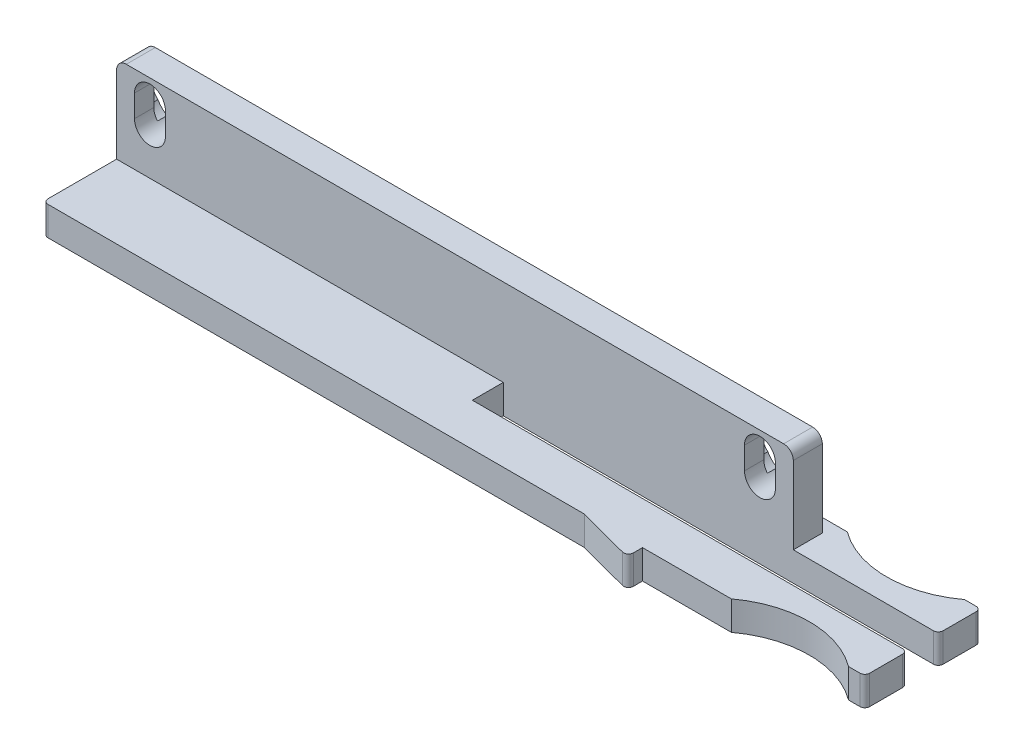
SolidWorks part; units mm, degrees
ref_plane "正面" through (0, 0, 0) normal (0, 0, 1) x (1, 0, 0)
ref_plane "平面" through (0, 0, 0) normal (0, 1, 0) x (1, 0, 0)
ref_plane "右側面" through (0, 0, 0) normal (1, 0, 0) x (0, 0, -1)
sketch "ｽｹｯﾁ2" plane through (0, 0, 0) normal (0, 1, 0) x (1, 0, 0)
  line L0 (70, 7.6) -> (40, 7.6)
  line L1 (0.5, 0) -> (56, 0)
  line L2 (0, 0.5) -> (0, 11.5)
  line L3 (0.5, 12) -> (70, 12)
  line L5 (40, 7.6) -> (40, 4.4)
  line L6 (40, 4.4) -> (70, 4.4)
  line L8 (56, 0) -> (61.3712, -1.4323)
  line L9 (62, -0.9492) -> (62, 0)
  line L10 (62, 0) -> (70, 0)
  line L11 (70, 12) -> (71.1837, 12)
  line L12 (85, 11.5) -> (85, 8.1)
  line L13 (84.5, 7.6) -> (70, 7.6)
  line L14 (70, 4.4) -> (84.5, 4.4)
  line L15 (85, 3.9) -> (85, 0.5)
  line L16 (84.5, 0) -> (83.3163, 0)
  line L17 (77.25, 12) -> (77.25, 20.2) construction
  line L18 (77.25, 12) -> (77.25, 10) construction
  line L19 (0, 6) -> (85, 6) construction
  line L20 (77.25, 0) -> (77.25, 2) construction
  line L21 (77.25, 0) -> (77.25, -8.2) construction
  line L22 (71.1837, 0) -> (70, 0)
  line L23 (83.3163, 12) -> (84.5, 12)
  arc A0 (61.3712, -1.4323) -> (62, -0.9492) centre (61.5, -0.9492) ccw
  arc A1 (71.1837, 12) -> (83.3163, 12) centre (77.25, 20.2) ccw
  arc A2 (71.1837, 0) -> (83.3163, 0) centre (77.25, -8.2) cw
  arc A3 (84.5, 12) -> (85, 11.5) centre (84.5, 11.5) cw
  arc A4 (85, 0.5) -> (84.5, 0) centre (84.5, 0.5) cw
  arc A5 (84.5, 4.4) -> (85, 3.9) centre (84.5, 3.9) cw
  arc A6 (85, 8.1) -> (84.5, 7.6) centre (84.5, 8.1) cw
  arc A7 (0.5, 0) -> (0, 0.5) centre (0.5, 0.5) cw
  arc A8 (0, 11.5) -> (0.5, 12) centre (0.5, 11.5) cw
  point P14 (62, -1.6)
  point P33 (77.25, 4.4)
  point P35 (77.25, 7.6)
  point P39 (85, 12)
  point P46 (85, 7.6)
  point P49 (0, 0)
  point P52 (0, 12)
  dimension "D8" = 0.5
  dimension "D12" = 0.5
  dimension "D13" = 0.5
  dimension "D14" = 0.5
  dimension "D1" = 70
  dimension "D2" = 15
  dimension "D3" = 3.2
  dimension "D4" = 30
  dimension "D5" = 8
  dimension "D6" = 6
  dimension "6" = 1.6
  dimension "D9" = 12
  dimension "D10" = 2
  dimension "D11" = 8.2
extrude "ﾎﾞｽ - 押し出し1" add sketch "ｽｹｯﾁ2" along normal blind 3
sketch "ｽｹｯﾁ4" plane through (0, 3, 0) normal (0, 1, 0) x (1, 0, 0)
  line L0 (0, 11.5) -> (0, 0.5) construction
  line L1 (70, 7.6) -> (0, 7.6)
  line L2 (70, 7.6) -> (70, 10.6)
  line L3 (70, 10.6) -> (0, 10.6)
  line L4 (0, 7.6) -> (0, 10.6)
  line L5 (40, 7.6) -> (84.5, 7.6) construction
  dimension "D1" = 3
  dimension "D2" = 70
extrude "ﾎﾞｽ - 押し出し2" add sketch "ｽｹｯﾁ4" along normal blind 9
sketch "ｽｹｯﾁ5" plane through (0, 0, -7.6) normal (0, 0, 1) x (1, 0, 0)
  line L0 (35, 12) -> (35, 8.7) construction
  line L1 (0, 12) -> (70, 12) construction
  line L2 (35, 8.7) -> (35, 3) construction
  line L4 (0.5, 3) -> (56, 3) construction
  line L7 (4.6, 8.7) -> (65.4, 8.7) construction
  line L10 (65.4, 8.7) -> (67.7, 8.7) construction
  line L14 (4.6, 8.7) -> (2.3, 8.7) construction
  line L15 (66.55, 7.55) -> (66.55, 9.85) construction
  line L16 (3.45, 7.55) -> (3.45, 9.85) construction
  arc A8 (64.3707, 9.9249) -> (64.3707, 7.4751) centre (65.4, 8.7) ccw
  arc A9 (65.3251, 6.5207) -> (67.7749, 6.5207) centre (66.55, 7.55) ccw
  arc A11 (5.6293, 7.4751) -> (5.6293, 9.9249) centre (4.6, 8.7) ccw
  arc A12 (1.2707, 9.9249) -> (1.2707, 7.4751) centre (2.3, 8.7) ccw
  arc A13 (2.2251, 6.5207) -> (4.6749, 6.5207) centre (3.45, 7.55) ccw
  arc A14 (67.7749, 10.8793) -> (65.3251, 10.8793) centre (66.55, 9.85) ccw
  arc A16 (68.7293, 7.4751) -> (68.7293, 9.9249) centre (67.7, 8.7) ccw
  arc A18 (64.3707, 7.4751) -> (65.3251, 6.5207) centre (66.55, 8.7) ccw
  arc A19 (67.7749, 6.5207) -> (68.7293, 7.4751) centre (66.55, 8.7) ccw
  arc A20 (68.7293, 9.9249) -> (67.7749, 10.8793) centre (66.55, 8.7) ccw
  arc A21 (65.3251, 10.8793) -> (64.3707, 9.9249) centre (66.55, 8.7) ccw
  arc A22 (1.2707, 7.4751) -> (2.2251, 6.5207) centre (3.45, 8.7) ccw
  arc A26 (4.6749, 10.8793) -> (2.2251, 10.8793) centre (3.45, 9.85) ccw
  arc A27 (2.2251, 10.8793) -> (1.2707, 9.9249) centre (3.45, 8.7) ccw
  arc A28 (5.6293, 9.9249) -> (4.6749, 10.8793) centre (3.45, 8.7) ccw
  arc A29 (4.6749, 6.5207) -> (5.6293, 7.4751) centre (3.45, 8.7) ccw
  point P9 (35, 8.7)
  point P10 (3.45, 8.7)
  point P13 (66.55, 8.7)
  point P17 (66.55, 8.7)
  point P20 (3.45, 8.7)
  dimension "D3" = 2.3
  dimension "D5" = 1.6
  dimension "5" = 5
  dimension "D1" = 5.7
  dimension "D2" = 63.1
extrude "ｶｯﾄ - 押し出し1" cut sketch "ｽｹｯﾁ5" against normal up to next
fillet "ﾌｨﾚｯﾄ1" radius 1 2 edges at (70, 12, -9.1) (0, 12, -9.1)
sketch "ｽｹｯﾁ6" plane through (0, 0, -7.6) normal (0, 0, 1) x (1, 0, 0)
  line L0 (1.85, 9.85) -> (1.85, 7.55)
  line L1 (5.05, 9.85) -> (5.05, 7.55)
  line L2 (64.95, 9.85) -> (64.95, 7.55)
  line L3 (68.15, 9.85) -> (68.15, 7.55)
  arc A42 (5.05, 9.85) -> (4.6749, 10.8793) centre (3.45, 9.85) ccw
  arc A43 (1.85, 7.55) -> (2.2251, 6.5207) centre (3.45, 7.55) ccw
  arc A53 (4.6749, 6.5207) -> (5.6293, 7.4751) centre (3.45, 8.7) ccw
  arc A54 (5.6293, 7.4751) -> (5.6293, 9.9249) centre (4.6, 8.7) ccw
  arc A55 (5.6293, 9.9249) -> (4.6749, 10.8793) centre (3.45, 8.7) ccw
  arc A56 (4.6749, 6.5207) -> (5.6293, 7.4751) centre (3.45, 8.7) ccw
  arc A57 (5.6293, 7.4751) -> (5.6293, 9.9249) centre (4.6, 8.7) ccw
  arc A58 (5.6293, 9.9249) -> (4.6749, 10.8793) centre (3.45, 8.7) ccw
  arc A62 (2.2251, 10.8793) -> (1.85, 9.85) centre (3.45, 9.85) ccw
  arc A63 (4.6749, 6.5207) -> (5.05, 7.55) centre (3.45, 7.55) ccw
  arc A64 (68.15, 9.85) -> (67.7749, 10.8793) centre (66.55, 9.85) ccw
  arc A65 (1.2707, 7.4751) -> (2.2251, 6.5207) centre (3.45, 8.7) ccw
  arc A66 (1.2707, 9.9249) -> (1.2707, 7.4751) centre (2.3, 8.7) ccw
  arc A67 (2.2251, 10.8793) -> (1.2707, 9.9249) centre (3.45, 8.7) ccw
  arc A68 (1.2707, 7.4751) -> (2.2251, 6.5207) centre (3.45, 8.7) ccw
  arc A69 (1.2707, 9.9249) -> (1.2707, 7.4751) centre (2.3, 8.7) ccw
  arc A70 (2.2251, 10.8793) -> (1.2707, 9.9249) centre (3.45, 8.7) ccw
  arc A71 (64.95, 7.55) -> (65.3251, 6.5207) centre (66.55, 7.55) ccw
  arc A81 (64.3707, 7.4751) -> (65.3251, 6.5207) centre (66.55, 8.7) ccw
  arc A82 (64.3707, 9.9249) -> (64.3707, 7.4751) centre (65.4, 8.7) ccw
  arc A83 (65.3251, 10.8793) -> (64.3707, 9.9249) centre (66.55, 8.7) ccw
  arc A84 (64.3707, 7.4751) -> (65.3251, 6.5207) centre (66.55, 8.7) ccw
  arc A85 (64.3707, 9.9249) -> (64.3707, 7.4751) centre (65.4, 8.7) ccw
  arc A86 (65.3251, 10.8793) -> (64.3707, 9.9249) centre (66.55, 8.7) ccw
  arc A90 (65.3251, 10.8793) -> (64.95, 9.85) centre (66.55, 9.85) ccw
  arc A91 (67.7749, 6.5207) -> (68.15, 7.55) centre (66.55, 7.55) ccw
  arc A93 (67.7749, 6.5207) -> (68.7293, 7.4751) centre (66.55, 8.7) ccw
  arc A94 (68.7293, 7.4751) -> (68.7293, 9.9249) centre (67.7, 8.7) ccw
  arc A95 (68.7293, 9.9249) -> (67.7749, 10.8793) centre (66.55, 8.7) ccw
  arc A96 (67.7749, 6.5207) -> (68.7293, 7.4751) centre (66.55, 8.7) ccw
  arc A97 (68.7293, 7.4751) -> (68.7293, 9.9249) centre (67.7, 8.7) ccw
  arc A98 (68.7293, 9.9249) -> (67.7749, 10.8793) centre (66.55, 8.7) ccw
  dimension "D1" = 0
  dimension "D2" = 0
  dimension "D3" = 0
  dimension "D4" = 0
extrude "ﾎﾞｽ - 押し出し3" add sketch "ｽｹｯﾁ6" against normal blind 2
